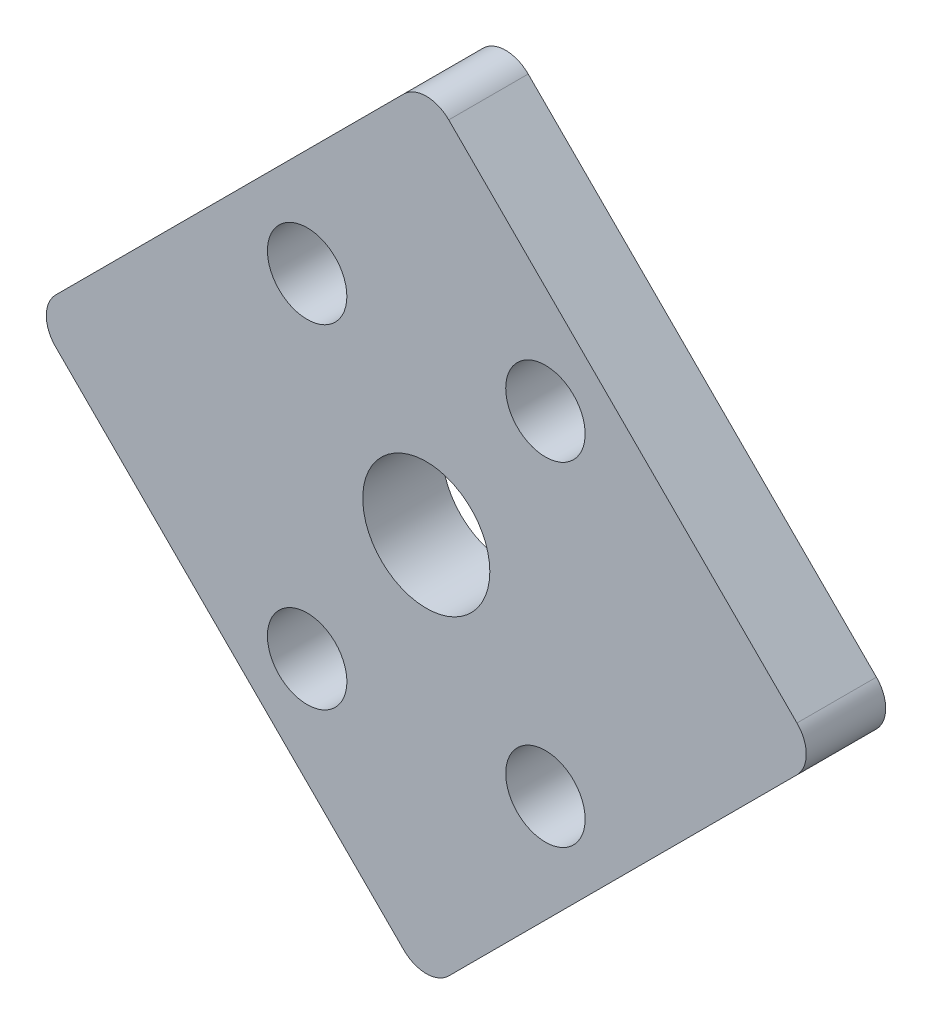
SolidWorks part; units mm, degrees
ref_plane "前视基准面" through (0, 0, 0) normal (0, 0, 1) x (1, 0, 0)
ref_plane "上视基准面" through (0, 0, 0) normal (0, 1, 0) x (1, 0, 0)
ref_plane "右视基准面" through (0, 0, 0) normal (1, 0, 0) x (0, 0, -1)
other "Configuration Table"
sketch "草图1" plane through (0, 0, 0) normal (0, 0, 1) x (1, 0, 0)
  line L0 (0, 0) -> (0, 24.7487) construction
  line L1 (0, -24.7487) -> (24.7487, 0)
  line L2 (24.7487, 0) -> (0, 24.7487)
  line L3 (0, 24.7487) -> (-24.7487, 0)
  line L4 (-24.7487, 0) -> (0, -24.7487)
  circle A0 centre (0, 0) radius 17.5 construction
  dimension "D1" = 35
extrude "凸台-拉伸1" add sketch "草图1" along normal blind 5
sketch "草图2" plane through (0, 0, 5) normal (0, 0, 1) x (1, 0, 0)
  line L0 (-24.7487, 0) -> (0, 0) construction
  line L1 (0, 0) -> (0, 24.7487) construction
  line L2 (0, 24.7487) -> (-24.7487, 0) construction
  line L3 (24.7487, 0) -> (0, 24.7487) construction
  circle A0 centre (0, 0) radius 4
  dimension "D1" = 8
extrude "切除-拉伸1" cut sketch "草图2" against normal blind 5
sketch "草图3" plane through (0, 0, 5) normal (0, 0, 1) x (1, 0, 0)
  line L0 (-24.7487, 0) -> (0, 0) construction
  line L1 (0, 0) -> (0, 24.7487) construction
sketch "草图5" plane through (0, 0, 5) normal (0, 0, 1) x (1, 0, 0)
  line L0 (0, 0) -> (0, 24.7487) construction
  line L1 (-24.7487, 0) -> (0, 0) construction
  line L2 (0, 0) -> (0, 15.7014) construction
  line L3 (0, 0) -> (-14.0094, 0) construction
  circle A5 centre (-7.5, 10.5) radius 2.5
  circle A8 centre (7.5, 10.5) radius 2.5
  circle A9 centre (7.5, -10.5) radius 2.5
  circle A10 centre (-7.5, -10.5) radius 2.5
  dimension "D1" = 5
  dimension "D2" = 7.5
  dimension "D3" = 10.5
extrude "切除-拉伸2" cut sketch "草图5" against normal through all
fillet "圆角1" radius 2 4 edges at (0, 24.7487, 2.5) (24.7487, 0, 2.5) (0, -24.7487, 2.5) (-24.7487, 0, 2.5)
